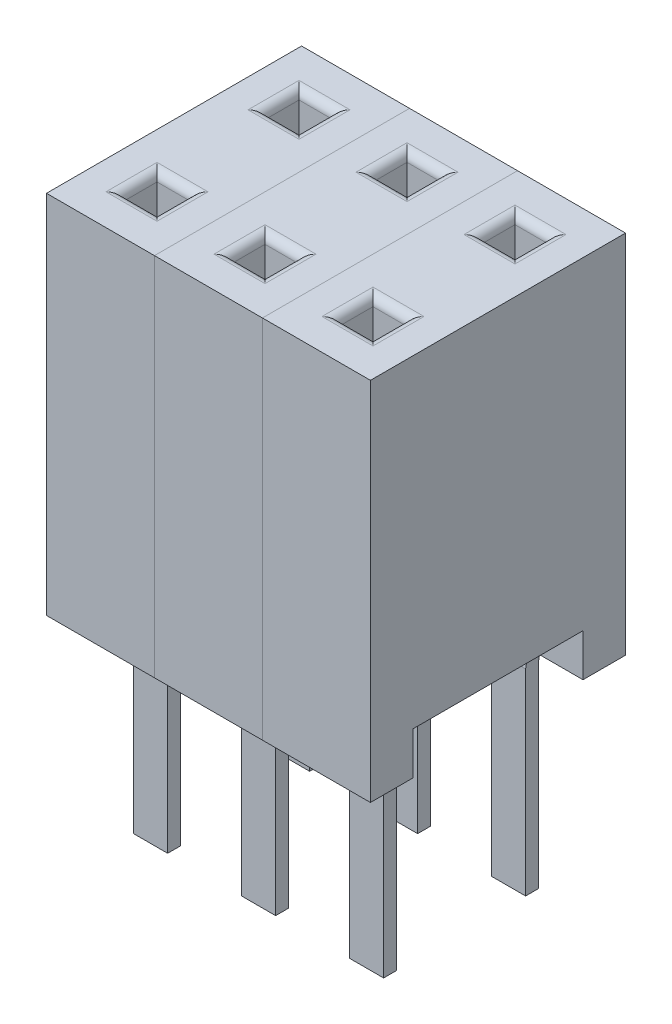
SolidWorks part; units mm, degrees
ref_plane "前视基准面" through (0, 0, 0) normal (0, 0, 1) x (1, 0, 0)
ref_plane "上视基准面" through (0, 0, 0) normal (0, 1, 0) x (1, 0, 0)
ref_plane "右视基准面" through (0, 0, 0) normal (1, 0, 0) x (0, 0, -1)
sketch "草图1" plane through (0, 0, 0) normal (0, 1, 0) x (1, 0, 0)
  line L1 (0.635, -1.5) -> (-0.635, -1.5)
  line L2 (0.635, -1.5) -> (0.635, 1.5)
  line L3 (0.635, 1.5) -> (-0.635, 1.5)
  line L4 (-0.635, -1.5) -> (-0.635, 1.5)
  line L5 (0.635, -1.5) -> (-0.635, 1.5) construction
  line L6 (0.635, 1.5) -> (-0.635, -1.5) construction
  point P0 (0, 0)
  dimension "D1" = 1.27
  dimension "D2" = 3
extrude "凸台-拉伸1" add sketch "草图1" along normal blind 4.3
sketch "草图3" plane through (0, 0, 0) normal (1, 0, 0) x (0, 0, -1)
  line L0 (1.5, 0) -> (-1.5, 0) construction
  line L1 (1, 0) -> (-1, 0)
  line L2 (1, 0) -> (1, 0.5)
  line L3 (1, 0.5) -> (-1, 0.5)
  line L4 (-1, 0) -> (-1, 0.5)
  line L5 (0, 1.1304) -> (0, -1.1304) construction
  line L6 (1.5, 4.3) -> (1.5, 0) construction
  point P10 (0, 0)
  dimension "D1" = 0.5
  dimension "D2" = 0.5
extrude "切除-拉伸2" cut sketch "草图3" against normal through all both and the other way through all
sketch "草图2" plane through (0, 4.3, 0) normal (0, 1, 0) x (1, 0, 0)
  line L1 (-0.2, -0.2) -> (0.2, -0.2)
  line L2 (-0.2, -0.2) -> (-0.2, 0.2)
  line L3 (-0.2, 0.2) -> (0.2, 0.2)
  line L4 (0.2, -0.2) -> (0.2, 0.2)
  line L5 (-0.2, -0.2) -> (0.2, 0.2) construction
  line L6 (-0.2, 0.2) -> (0.2, -0.2) construction
  point P0 (0, 0)
  dimension "D1" = 0.4
extrude "切除-拉伸1" [suppressed] cut sketch "草图2" against normal offset from surface (2.9 mm away) 1.5
sketch "草图4" plane through (0, 0, 0) normal (1, 0, 0) x (0, 0, -1)
  line L0 (-0.85, 0.409) -> (0.075, 0.109)
  line L1 (1, 0.5) -> (-1, 0.5) construction
  line L2 (0.075, 0.109) -> (0.075, -2.3)
  line L3 (0.075, -2.3) -> (-0.075, -2.3)
  line L4 (-0.075, -2.3) -> (-0.075, 0)
  line L5 (-0.075, 0) -> (-1, 0.3)
  line L6 (-1, 0.5) -> (-1, 0) construction
  line L7 (-0.075, 0) -> (-0.0287, 0.1427) construction
  line L8 (-0.85, 0.409) -> (-0.85, 0.5)
  line L9 (-0.85, 0.5) -> (-1, 0.5)
  line L10 (0, 3.0819) -> (0, -3.0819) construction
  line L11 (-1, 0.5) -> (-1, 0.3)
  point P17 (0, 0)
  dimension "D1" = 2.3
  dimension "D2" = 0.15
  dimension "D3" = 0.2
extrude "凸台-拉伸2" [suppressed] add sketch "草图4" along normal mid plane 0.4
fillet "圆角1" [suppressed] radius 0.1
pattern_linear "阵列(线性)1" [suppressed] count 3 spacing 1.27 count 2 spacing 1.27
sketch "草图5" plane through (0, 4.3, 0) normal (0, 1, 0) x (1, 0, 0)
  line L0 (0, 1.4076) -> (0, -1.4076) construction
  line L1 (-0.2, 1.035) -> (0.2, 1.035)
  line L2 (-0.2, 1.035) -> (-0.2, 0.635)
  line L3 (-0.2, 0.635) -> (0.2, 0.635)
  line L4 (0.2, 1.035) -> (0.2, 0.635)
  line L5 (-0.2, -0.635) -> (0.2, -0.635)
  line L6 (-0.2, -0.635) -> (-0.2, -1.035)
  line L7 (-0.2, -1.035) -> (0.2, -1.035)
  line L8 (0.2, -0.635) -> (0.2, -1.035)
  line L9 (-1.1668, 0) -> (1.1668, 0) construction
  point P12 (0, 0)
  point P15 (0, 0)
  dimension "D1" = 1.27
  dimension "D2" = 0.4
extrude "切除-拉伸3" cut sketch "草图5" against normal offset from surface (2.8 mm away) 1.5 up to plane "上视基准面"
fillet "圆角2" radius 0.1 8 edges at (-0.2, 4.3, 0.835) (0, 4.3, 1.035) (0.2, 4.3, 0.835) (0, 4.3, 0.635) (-0.2, 4.3, -0.835) (0, 4.3, -0.635) (0.2, 4.3, -0.835) (0, 4.3, -1.035)
sketch "草图6" plane through (0, 0, 0) normal (1, 0, 0) x (0, 0, -1)
  line L0 (1, 0.5) -> (0.91, 0)
  line L1 (1, 0) -> (1, 0.5) construction
  line L2 (0.91, 0) -> (0.91, -2.3)
  line L3 (0.91, -2.3) -> (0.76, -2.3)
  line L4 (0.76, -2.3) -> (0.76, 0.0134)
  line L5 (0.76, 0.0134) -> (0.8476, 0.5)
  line L6 (0.9952, 0.4734) -> (0.8476, 0.5) construction
  line L7 (0, 2.9618) -> (0, -2.9618) construction
  line L8 (1, 0.5) -> (-1, 0.5) construction
  line L9 (0.835, 1.5) -> (0.835, -3.1463) construction
  line L10 (0.635, 1.5) -> (1.035, 1.5) construction
  line L11 (-0.835, 1.5) -> (-0.835, -3.1463) construction
  line L12 (-1.035, 1.5) -> (-0.635, 1.5) construction
  line L13 (1, 0.5) -> (0.8476, 0.5)
  line L14 (-0.9952, 0.4734) -> (-0.8476, 0.5) construction
  line L15 (-0.76, 0.0134) -> (-0.8476, 0.5)
  line L16 (-0.76, -2.3) -> (-0.76, 0.0134)
  line L17 (-0.91, -2.3) -> (-0.76, -2.3)
  line L18 (-0.91, 0) -> (-0.91, -2.3)
  line L19 (-1, 0.5) -> (-0.91, 0)
  line L20 (-1, 0.5) -> (-0.8476, 0.5)
  point P14 (0, 0)
  dimension "D1" = 0.15
  dimension "D2" = 2.3
extrude "凸台-拉伸3" add sketch "草图6" along normal mid plane 0.4
pattern_linear "阵列(线性)2" count 3 spacing 1.27 along (1, 0, 0) of bodies 114
